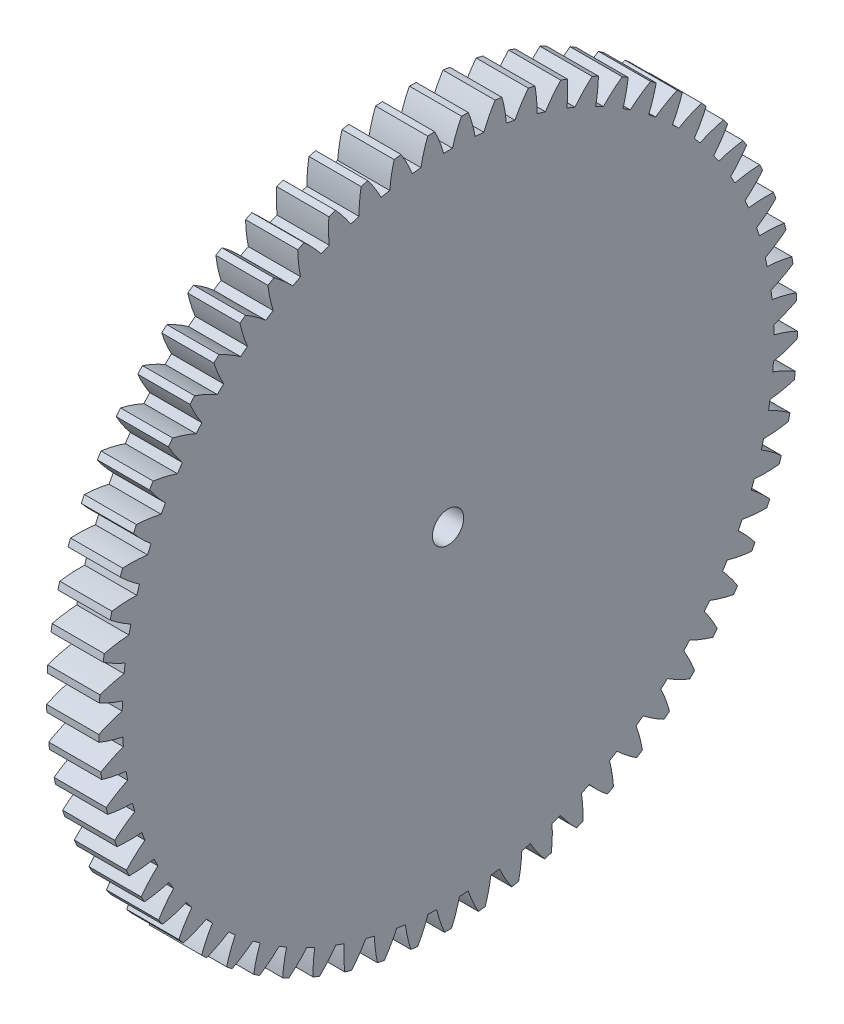
SolidWorks part; units mm, degrees
ref_plane "Plane1" through (0, 0, 0) normal (0, 0, 1) x (1, 0, 0)
ref_plane "Plane2" through (0, 0, 0) normal (0, 1, 0) x (1, 0, 0)
ref_plane "Plane3" through (0, 0, 0) normal (1, 0, 0) x (0, 0, -1)
sketch "HoldingSke" plane through (0, 0, 0) normal (0, 1, 0) x (1, 0, 0)
  line L0 (0, 0) -> (0.2113, -0.4532)
  line L1 (-15, 0) -> (100, 0) construction
  line L2 (0, 0) -> (-2.1039, 2.3779)
  line L3 (0, 0) -> (-11.863, 4.5341)
  line L4 (0, 0) -> (3.6497, 7.8269)
  line L5 (0, 0) -> (-46.8476, -17.4728)
  line L6 (0, 0) -> (-8.2896, -5.593)
  line L7 (-2.1039, 2.3779) -> (8.6586, 51.2059)
  line L8 (-76.2, 54.61) -> (-75.2, 54.61)
  line L9 (-71.009, 38.7566) -> (-53.1078, 45.2721)
  line L10 (-76.2, 71.12) -> (104.1128, 71.12)
  line L11 (0, 0) -> (-10, 0)
  line L12 (-76.2, 101.6) -> (-76.133, 101.6)
  line L13 (24.9733, 27.94) -> (52.9518, 28.4284)
  line L14 (24.9733, 27.94) -> (24.9743, 27.94)
  line L15 (24.9733, 27.94) -> (100.4006, 29.5858)
  line L16 (-63.627, -2) -> (-12.827, -2)
  circle A0 centre (0, 0) radius 3
  circle A1 centre (0, 0) radius 4
  circle A2 centre (0, 0) radius 4
  circle A3 centre (0, 0) radius 3
  dimension "MHD" = 8
  dimension "Hub_dia" = 8
  dimension "Bore" = 6
  dimension "MBD" = 6
  dimension "Num_teeth" = 65
  dimension "Pitch" = 0.5
  dimension "Overall_len" = 50
  dimension "Show_teeth" = 65
  dimension "Thickness" = 10
  dimension "OAL" = 50.0001
  dimension "T_dim" = 1
  dimension "Ap" = 20
  dimension "H" = 19.05
  dimension "Pitch_radius" = 180.3128
  dimension "Width" = 10
  dimension "Backlash" = 0.067
  dimension "Addendum_fac" = 1
  dimension "Dedendum_fac" = 1.25
  dimension "Clearance_fac" = 0.25
  dimension "Dedendum_add" = 0.001
  dimension "Module" = 2
sketch "BasProSke" plane through (0, 0, 0) normal (0, 1, 0) x (1, 0, 0)
  line L0 (-10, 0) -> (60, 0) construction
  line L1 (0, 0) -> (0, 67)
  line L2 (0, 0) -> (10, 0)
  line L3 (10, 0) -> (10, 67)
  line L4 (10, 67) -> (0, 67)
  dimension "Thickness" = 10
  dimension "Diameter" = 134
revolve "Base-Revolve" add sketch "BasProSke" angle 360 about L0
sketch "TooCutSke" plane through (0, 0, 0) normal (1, 0, 0) x (0, 0, -1)
  line L1 (0, 0) -> (0, 107) construction
  line L2 (0, 0) -> (-1.6879, 64.9781) construction
  line L3 (0, 0) -> (-6.2792, 129.8157) construction
  line L4 (-1.6879, 64.9781) -> (-3.1396, 64.9079) construction
  arc A0 (0.8396, 62.4934) -> (-0.8396, 62.4934) centre (0, 0) ccw
  arc A1 (2.5838, 66.9756) -> (-2.5838, 66.9756) centre (0, 0) ccw
  circle A2 centre (0, 0) radius 65 construction
  circle A3 centre (0, 0) radius 61.08 construction
  arc A4 (-0.8396, 62.4934) -> (-2.5838, 66.9756) centre (-25.8379, 55.3459) ccw
  arc A5 (2.5838, 66.9756) -> (0.8396, 62.4934) centre (25.8379, 55.3459) ccw
  dimension "Root_dia" = 124.998
  dimension "Overcut_dia" = 134.0508
  dimension "Pitch_dia" = 130
  dimension "Base_dia" = 122.16
  dimension "Flank_rad" = 26
  dimension "Half_ang" = 2.769
  dimension "Half_CT" = 1.4534
extrude "ToothCut" cut sketch "TooCutSke" along normal through all
fillet "Breaks" [suppressed] radius 0.04
fillet "RootFillets" [suppressed] radius 0.501
pattern_circular "TeethCuts" count 65 every 5.538 about axis through (-10, 0, 0) along (1, 0, 0) of "ToothCut", "RootFillets", "Breaks"
sketch "HubNeaOneSke" plane through (0, 0, 0) normal (-1, 0, 0) x (0, 0, 1)
  circle A0 centre (0, 0) radius 4
  dimension "Diameter" = 8
extrude "HubNearOne" add sketch "HubNeaOneSke" along normal blind 40.0001
sketch "HubNeaBotSke" plane through (0, 0, 0) normal (-1, 0, 0) x (0, 0, 1)
  circle A0 centre (0, 0) radius 4
  dimension "Diameter" = 8
extrude "HubNearBoth" [suppressed] add sketch "HubNeaBotSke" along normal blind 20
ref_plane "FarPln" through (10, 0, 0) normal (1, 0, 0) x (0, 0, -1)
sketch "HubFarSke" plane through (10, 0, 0) normal (1, 0, 0) x (0, 0, -1)
  circle A0 centre (0, 0) radius 4
  dimension "Diameter" = 8
extrude "HubFar" [suppressed] add sketch "HubFarSke" along normal blind 20
sketch "BorSke" plane through (0, 0, 0) normal (1, 0, 0) x (0, 0, -1)
  circle A0 centre (0, 0) radius 3
  dimension "Diameter" = 6
extrude "Bore" cut sketch "BorSke" along normal mid plane 100.0001
sketch "KeySke" plane through (0, 0, 0) normal (1, 0, 0) x (0, 0, -1)
  line L0 (-1, 0) -> (-1, 4)
  line L1 (-1, 4) -> (1, 4)
  line L2 (1, 4) -> (1, 0)
  line L3 (0, 0) -> (0, 34) construction
  line L4 (-1, 0) -> (1, 0)
  dimension "Offset" = 4
  dimension "Width" = 2
extrude "Keyway" [suppressed] cut sketch "KeySke" along normal mid plane 100.0001
pattern_circular "Keyway2" [suppressed] count 2 every 90 about axis through (-10, 0, 0) along (1, 0, 0)
equation "' \"Module@HoldingSke\" = 6.35"
equation "' \"Num_teeth@HoldingSke\" = 12"
equation "' \"Ap@HoldingSke\" =  20"
equation "' \"Ap@HoldingSke\" = 20"
equation "' \"Width@HoldingSke\" = 0.5 * 25.4"
equation "' \"Hub_dia@HoldingSke\"= 1 * 25.4"
equation "' \"Hub_dia@HoldingSke\" = 1 * 25.4"
equation "' \"Overall_len@HoldingSke\" = 1.0 * 25.4"
equation "' \"Bore@HoldingSke\" = 0.75 * 25.4"
equation "' \"T_dim@HoldingSke\" = 0.1 * 25.4"
equation "' \"Width@KeySke\" = 0.25 * 25.4"
equation "' \"Show_teeth@HoldingSke\" = 13"
equation "' \"Backlash@HoldingSke\" = 0.009 * 25.4"
equation "' \"Addendum_fac@HoldingSke\" = 1.0"
equation "' \"Dedendum_fac@HoldingSke\" = 1.25"
equation "' \"Dedendum_add@HoldingSke\" = 0.00005 * 25.4"
equation "' \"Clearance_fac@HoldingSke\" = 0.25"
equation "\"Pitch@HoldingSke\" = 1 / \"Module@HoldingSke\""
equation "\"Overcut_dia@TooCutSke\" = (\"Num_teeth@HoldingSke\" + 2 * \"Addendum_fac@HoldingSke\") / \"Pitch@HoldingSke\" + 0.002 * 25.4"
equation "\"Pitch_dia@TooCutSke\" = \"Num_teeth@HoldingSke\" / \"Pitch@HoldingSke\""
equation "\"Base_dia@TooCutSke\" = \"Num_teeth@HoldingSke\" / \"Pitch@HoldingSke\" * cos((\"Ap@HoldingSke\"  * 3.14159265 / 180))"
equation "\"Root_dia@TooCutSke\" = (\"Num_teeth@HoldingSke\" + 2) / \"Pitch@HoldingSke\" - 2 * (\"Addendum_fac@HoldingSke\" + \"Dedendum_fac@HoldingSke\") / \"Pitch@HoldingSke\" - \"Dedendum_add@HoldingSke\" * 2"
equation "\"Half_ang@TooCutSke\" = 180 / \"Num_teeth@HoldingSke\""
equation "\"Half_CT@TooCutSke\" = \"Num_teeth@HoldingSke\" / \"Pitch@HoldingSke\" * sin((3.14159265 / 2 / \"Num_teeth@HoldingSke\")) / 2 - 7 * \"Backlash@HoldingSke\" / 4"
equation "\"Flank_rad@TooCutSke\" = \"Num_teeth@HoldingSke\" / \"Pitch@HoldingSke\" / 5"
equation "\"Radius@RootFillets\" = \"Clearance_fac@HoldingSke\" / \"Pitch@HoldingSke\" + \"Dedendum_add@HoldingSke\""
equation "\"Break_rad@Breaks\" = 0.02 / \"Pitch@HoldingSke\""
equation "\"Thickness@HoldingSke\" = \"Width@HoldingSke\""
equation "\"OAL@HoldingSke\" = \"Thickness@HoldingSke\""
equation "\"MHD@HoldingSke\" = (\"Num_teeth@HoldingSke\" + 2) / \"Pitch@HoldingSke\" - 2 * (\"Addendum_fac@HoldingSke\" + \"Dedendum_fac@HoldingSke\")  / \"Pitch@HoldingSke\" - \"Dedendum_add@HoldingSke\" * 2"
equation "\"MBD@HoldingSke\" = (\"Num_teeth@HoldingSke\" + 2) / \"Pitch@HoldingSke\" - 2 * (\"Addendum_fac@HoldingSke\" + \"Dedendum_fac@HoldingSke\")  / \"Pitch@HoldingSke\" - \"Dedendum_add@HoldingSke\" * 2 - 0.002 * 25.4"
equation "\"MHD@HoldingSke\" = ((sgn( \"MHD@HoldingSke\" - \"Hub_dia@HoldingSke\" )-1)*( \"MHD@HoldingSke\" - \"Hub_dia@HoldingSke\" ))/-2+ \"Hub_dia@HoldingSke\""
equation "\"MBD@HoldingSke\" = ((sgn( \"MBD@HoldingSke\" - \"Bore@HoldingSke\" )-1)*( \"MBD@HoldingSke\" - \"Bore@HoldingSke\" ))/-2+ \"Bore@HoldingSke\""
equation "\"OAL@HoldingSke\" = ((sgn( \"OAL@HoldingSke\" - \"Overall_len@HoldingSke\" )+1)*( \"OAL@HoldingSke\" - \"Overall_len@HoldingSke\" ))/2 + \"Overall_len@HoldingSke\" + 0.000002 * 25.4"
equation "\"Num_teeth@TeethCuts\" = int( \"Show_teeth@HoldingSke\" ) + 1"
equation "\"Num_teeth@TeethCuts\" = ((sgn( \"Num_teeth@TeethCuts\" - \"Num_teeth@HoldingSke\" )-1)*( \"Num_teeth@TeethCuts\" - \"Num_teeth@HoldingSke\" ))/-2+ \"Num_teeth@HoldingSke\""
equation "\"Num_teeth@TeethCuts\" = ((sgn( \"Num_teeth@TeethCuts\" - 2.0)+1)*( \"Num_teeth@TeethCuts\" - 2.0))/2 +2.0"
equation "\"Angle@TeethCuts\" = 360.0 / \"Num_teeth@HoldingSke\""
equation "\"Diameter@BasProSke\" = (\"Num_teeth@HoldingSke\" + 2 * \"Addendum_fac@HoldingSke\") / \"Pitch@HoldingSke\""
equation "\"Thickness@BasProSke\"  = \"Thickness@HoldingSke\""
equation "' \"Fillet_rad@BasProSke\" =  \"Thickness@HoldingSke\" * 0.05"
equation "' \"Fillet_rad@BasProSke\" = \"Thickness@HoldingSke\" * 0.05"
equation "\"MHD@HoldingSke\" = ((sgn( \"MHD@HoldingSke\" - \"Root_dia@TooCutSke\" )-1)*( \"MHD@HoldingSke\" - \"Root_dia@TooCutSke\" ))/-2+ \"Root_dia@TooCutSke\""
equation "\"Diameter@HubNeaOneSke\" = \"MHD@HoldingSke\""
equation "\"Length@HubNearOne\" = \"OAL@HoldingSke\" - \"Thickness@BasProSke\""
equation "\"Diameter@HubNeaBotSke\" = \"MHD@HoldingSke\""
equation "\"Length@HubNearBoth\" = ( \"OAL@HoldingSke\" - \"Thickness@BasProSke\" ) / 2.0"
equation "\"Thickness@FarPln\" = \"Thickness@BasProSke\""
equation "\"Diameter@HubFarSke\" = \"MHD@HoldingSke\""
equation "\"Length@HubFar\" = ( \"OAL@HoldingSke\" - \"Thickness@BasProSke\" ) / 2.0"
equation "\"Diameter@BorSke\" = \"MBD@HoldingSke\""
equation "\"D1@Bore\" = \"OAL@HoldingSke\" * 2.0"
equation "\"D1@Keyway\" = \"OAL@HoldingSke\" * 2.0"
equation "\"Offset@KeySke\" = \"T_dim@HoldingSke\" + \"MBD@HoldingSke\" / 2.0"
